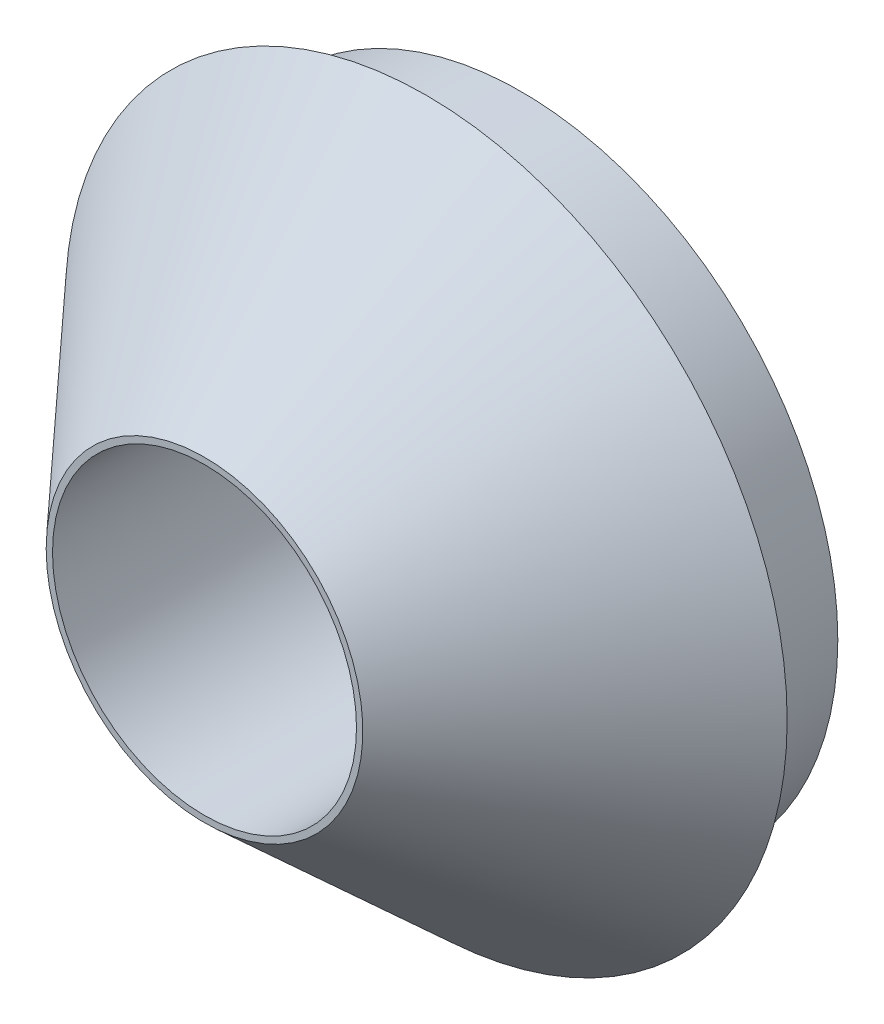
SolidWorks part; units mm, degrees
ref_plane "Front Plane" through (0, 0, 0) normal (0, 0, 1) x (1, 0, 0)
ref_plane "Top Plane" through (0, 0, 0) normal (0, 1, 0) x (1, 0, 0)
ref_plane "Right Plane" through (0, 0, 0) normal (1, 0, 0) x (0, 0, -1)
sketch "Sketch1" plane through (0, 0, 0) normal (0, 1, 0) x (1, 0, 0)
  line L0 (0, 0) -> (6.35, 0)
  line L1 (6.35, 0) -> (14.478, 8.89)
  line L2 (14.478, 8.89) -> (12.7, 8.89)
  line L3 (12.7, 8.89) -> (12.7, 12.7)
  line L4 (12.7, 12.7) -> (0, 12.7)
  line L5 (0, 12.7) -> (0, 0)
  dimension "D1" = 6.35
  dimension "D2" = 12.7
  dimension "D3" = 12.7
  dimension "D4" = 1.778
  dimension "D5" = 3.81
revolve "Revolve1" add sketch "Sketch1" angle 360 about L5
sketch "Sketch2" plane through (0, 0, -12.7) normal (0, 0, -1) x (-1, 0, 0)
  circle A0 centre (0, 0) radius 6.096
  dimension "D1" = 12.192
extrude "Cut-Extrude1" cut sketch "Sketch2" against normal blind 12.7
